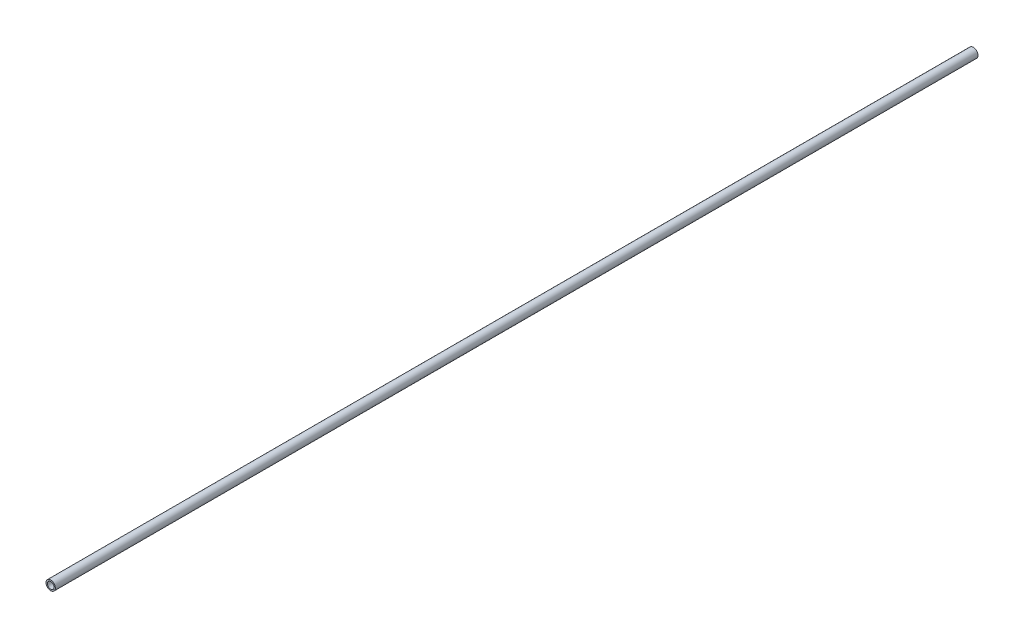
SolidWorks part; units mm, degrees
ref_plane "Front Plane" through (0, 0, 0) normal (0, 0, 1) x (1, 0, 0)
ref_plane "Top Plane" through (0, 0, 0) normal (0, 1, 0) x (1, 0, 0)
ref_plane "Right Plane" through (0, 0, 0) normal (1, 0, 0) x (0, 0, -1)
sketch "Sketch2" plane through (0, 0, 0) normal (0, 0, 1) x (1, 0, 0)
  circle A0 centre (0, 0) radius 1.25
  circle A1 centre (0, 0) radius 1.75
  dimension "D1" = 2.5
  dimension "D2" = 3.5
extrude "Boss-Extrude1" add sketch "Sketch2" against normal blind 345
